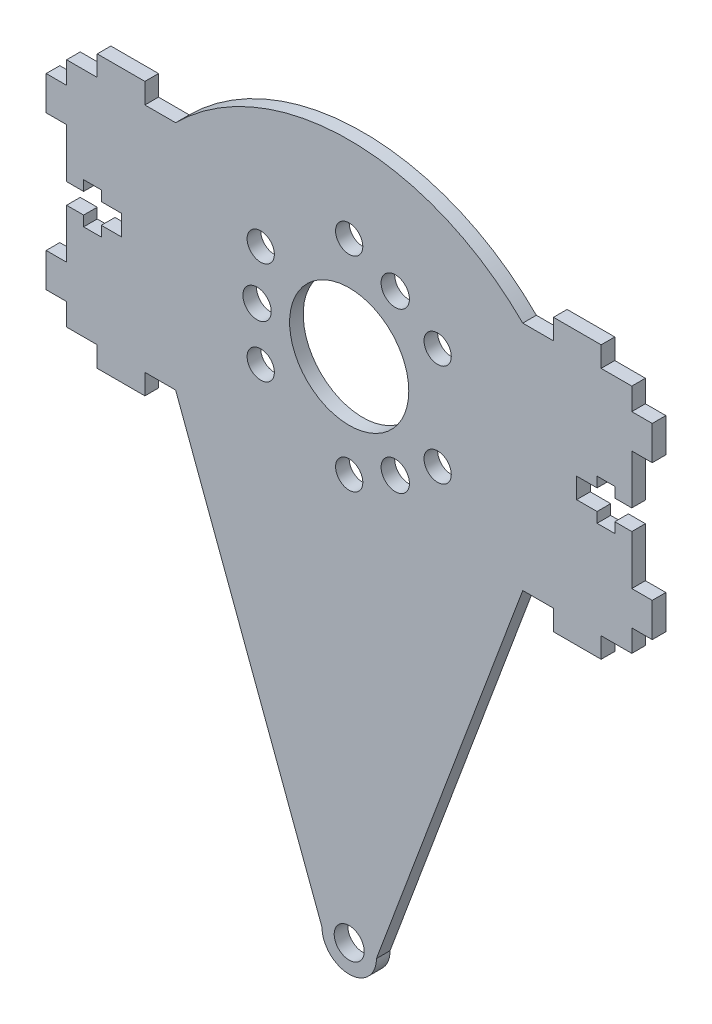
SolidWorks part; units mm, degrees
ref_plane "前视基准面" through (0, 0, 0) normal (0, 0, 1) x (1, 0, 0)
ref_plane "上视基准面" through (0, 0, 0) normal (0, 1, 0) x (1, 0, 0)
ref_plane "右视基准面" through (0, 0, 0) normal (1, 0, 0) x (0, 0, -1)
sketch "草图1" plane through (0, 0, 0) normal (0, 0, 1) x (1, 0, 0)
  line L0 (41.5, 13.75) -> (41.5, 17)
  line L205 (-30, 17) -> (-25.489, 17)
  line L310 (-37, 20) -> (-30, 20)
  line L325 (-30, 17) -> (-30, 20)
  line L326 (-37, 20) -> (-37, 17)
  line L337 (-41.5, 1.5) -> (-41.5, 8.75)
  line L338 (-41.5, 8.75) -> (-44.5, 8.75)
  line L340 (-44.5, 13.75) -> (-41.5, 13.75)
  line L341 (-41.5, 13.75) -> (-41.5, 17)
  line L346 (-41.5, -1.5) -> (-41.5, -8.75)
  line L368 (-37, -20) -> (-37, -17)
  line L369 (-30, -17) -> (-30, -20)
  line L372 (44.5, -8.75) -> (44.5, -13.75)
  line L373 (44.5, 13.75) -> (44.5, 8.75)
  line L374 (30, -17) -> (25.489, -17)
  line L375 (37, -20) -> (30, -20)
  line L378 (30, -17) -> (30, -20)
  line L379 (37, -20) -> (37, -17)
  line L380 (41.5, -1.5) -> (41.5, -8.75)
  line L381 (41.5, -8.75) -> (44.5, -8.75)
  line L382 (-37, -20) -> (-30, -20)
  line L383 (-30, -17) -> (-25.489, -17)
  line L384 (-44.5, 13.75) -> (-44.5, 8.75)
  line L386 (41.5, 17) -> (37, 17)
  line L388 (44.5, 13.75) -> (41.5, 13.75)
  line L389 (41.5, 8.75) -> (44.5, 8.75)
  line L390 (41.5, 1.5) -> (41.5, 8.75)
  line L391 (37, 20) -> (37, 17)
  line L392 (30, 17) -> (30, 20)
  line L393 (37, 20) -> (30, 20)
  line L394 (30, 17) -> (25.489, 17)
  line L396 (44.5, -13.75) -> (41.5, -13.75)
  line L397 (41.5, -13.75) -> (41.5, -17)
  line L398 (-39, -1.5) -> (-39, -3)
  line L399 (-33.4, 1.5) -> (-33.4, -1.5)
  line L400 (-39, 1.5) -> (-39, 3)
  line L401 (-41.5, 1.5) -> (-39, 1.5)
  line L402 (-39, -3) -> (-36.4, -3)
  line L403 (-36.4, -3) -> (-36.4, -1.5)
  line L404 (-36.4, -1.5) -> (-33.4, -1.5)
  line L405 (-36.4, 1.5) -> (-33.4, 1.5)
  line L406 (-36.4, 3) -> (-36.4, 1.5)
  line L407 (-39, 3) -> (-36.4, 3)
  line L408 (-39, -1.5) -> (-41.5, -1.5)
  line L409 (39, -1.5) -> (41.5, -1.5)
  line L410 (39, 3) -> (36.4, 3)
  line L411 (36.4, 3) -> (36.4, 1.5)
  line L412 (36.4, 1.5) -> (33.4, 1.5)
  line L413 (36.4, -1.5) -> (33.4, -1.5)
  line L414 (36.4, -3) -> (36.4, -1.5)
  line L415 (39, -3) -> (36.4, -3)
  line L416 (41.5, 1.5) -> (39, 1.5)
  line L417 (39, 1.5) -> (39, 3)
  line L418 (33.4, 1.5) -> (33.4, -1.5)
  line L419 (39, -1.5) -> (39, -3)
  line L423 (-41.5, -8.75) -> (-44.5, -8.75)
  line L424 (-44.5, -8.75) -> (-44.5, -13.75)
  line L425 (-44.5, -13.75) -> (-41.5, -13.75)
  line L437 (-4, -74.5579) -> (-25.489, -17)
  line L438 (4, -74.5579) -> (25.489, -17)
  line L439 (37, -17) -> (41.5, -17)
  line L440 (-41.5, 17) -> (-37, 17)
  line L441 (-41.5, -13.75) -> (-41.5, -17)
  line L442 (-41.5, -17) -> (-37, -17)
  circle A15 centre (0, -15) radius 2
  circle A16 centre (-12.9904, -7.5) radius 2
  circle A17 centre (-12.9904, 7.5) radius 2
  circle A18 centre (0, 15) radius 2
  circle A19 centre (12.9904, 7.5) radius 2
  circle A20 centre (12.9904, -7.5) radius 2
  circle A21 centre (-13.53, 0) radius 2.08
  circle A22 centre (6.765, 11.7173) radius 2.08
  circle A23 centre (6.765, -11.7173) radius 2.08
  circle A24 centre (0, 0) radius 8.75
  arc A27 (-25.489, 17) -> (25.489, 17) centre (0, -8.489) cw
  circle A30 centre (0, -74.5579) radius 2.2
  arc A32 (-4, -74.5579) -> (4, -74.5579) centre (0, -74.5579) ccw
  point P76 (-39.5, -17)
  dimension "D1" = 3
  dimension "D2" = 6
extrude "凸台-拉伸2" add sketch "草图1" along normal blind 2
sketch "草图2" plane through (41.5, 0, 0) normal (1, 0, 0) x (0, 0, -1)
  line L0 (-1, 1.5) -> (-1, -1.5)
  line L1 (-2, 1.5) -> (0, 1.5) construction
  line L2 (-2, -1.5) -> (0, -1.5) construction
  circle A0 centre (-1, 0) radius 1.5
sketch "草图3" plane through (-41.5, 0, 0) normal (-1, 0, 0) x (0, 0, 1)
  line L0 (1, 1.5) -> (1, -1.5)
  line L1 (2, 1.5) -> (0, 1.5) construction
  line L2 (2, -1.5) -> (0, -1.5) construction
  circle A0 centre (1, 0) radius 1.5
